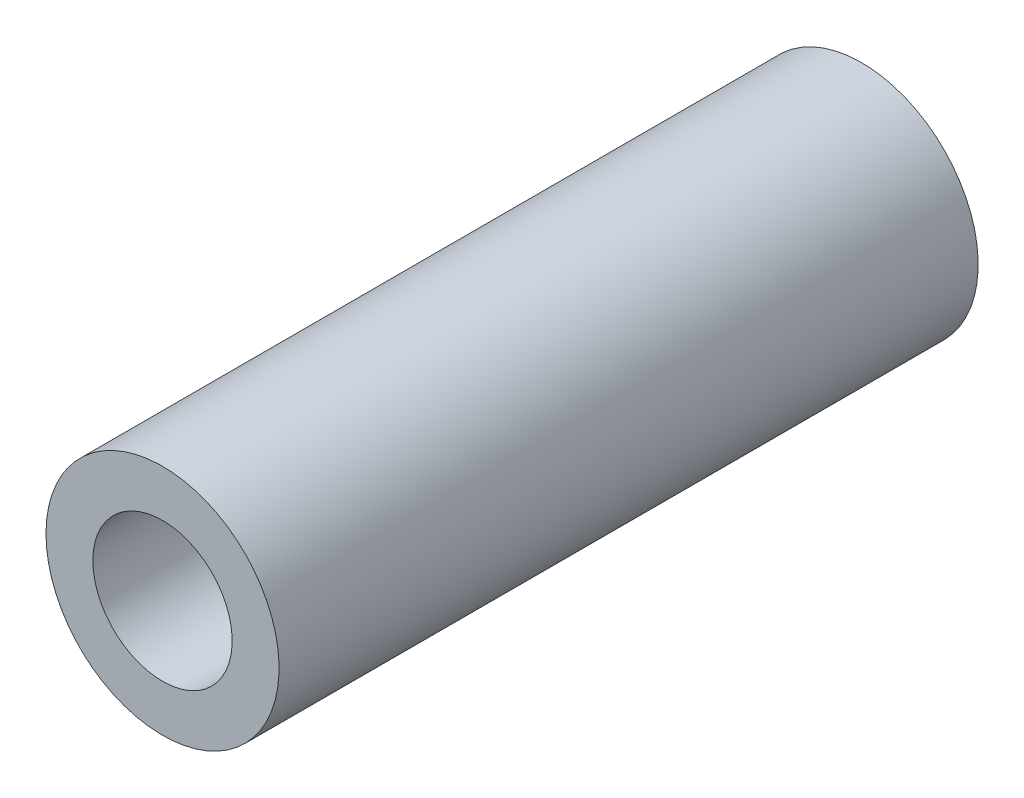
SolidWorks part; units mm, degrees
ref_plane "Front Plane" through (0, 0, 0) normal (0, 0, 1) x (1, 0, 0)
ref_plane "Top Plane" through (0, 0, 0) normal (0, 1, 0) x (1, 0, 0)
ref_plane "Right Plane" through (0, 0, 0) normal (1, 0, 0) x (0, 0, -1)
sketch "Sketch1" plane through (0, 0, 0) normal (0, 0, 1) x (1, 0, 0)
  circle A0 centre (0, 0) radius 3.175
  circle A1 centre (0, 0) radius 1.8986
  dimension "D1" = 6.35
  dimension "D2" = 3.7973
extrude "Boss-Extrude1" add sketch "Sketch1" along normal blind 19.05
